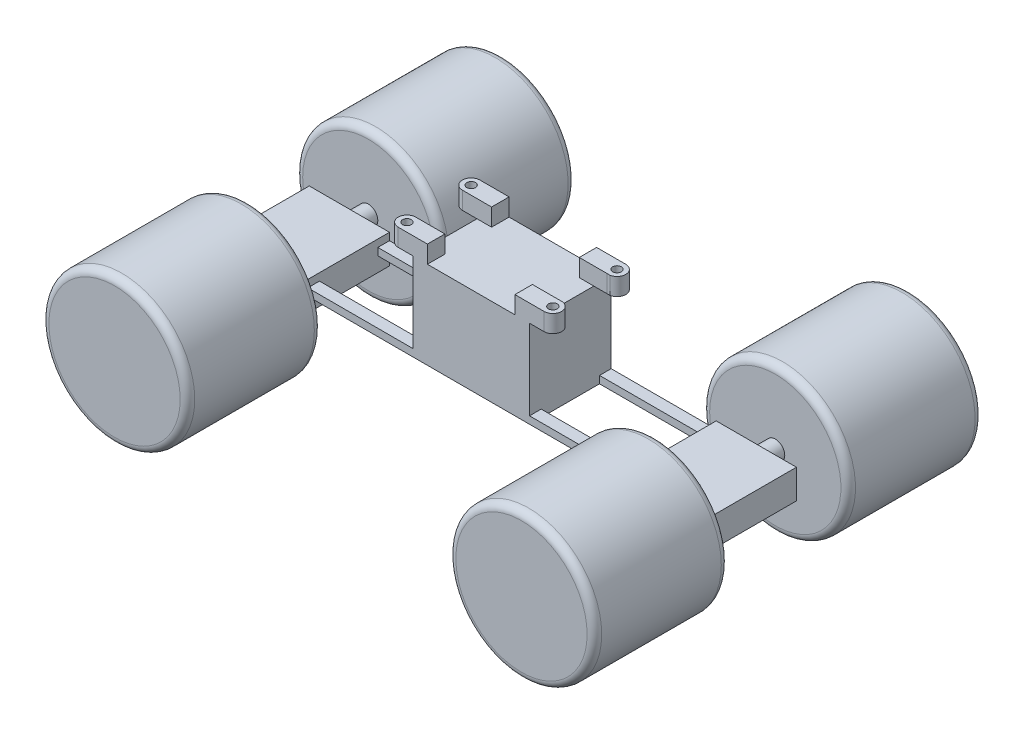
SolidWorks part; units mm, degrees
ref_plane "Front Plane" through (0, 0, 0) normal (0, 0, 1) x (1, 0, 0)
ref_plane "Top Plane" through (0, 0, 0) normal (0, 1, 0) x (1, 0, 0)
ref_plane "Right Plane" through (0, 0, 0) normal (1, 0, 0) x (0, 0, -1)
sketch "Sketch1" plane through (0, 0, 0) normal (0, 1, 0) x (1, 0, 0)
  line L0 (0, 50) -> (20, 50)
  line L1 (0, 38) -> (20, 38)
  line L2 (0, 6) -> (20, 6)
  line L3 (20, 6) -> (20, -6)
  line L4 (20, -6) -> (0, -6)
  line L5 (20, 50) -> (20, 38)
  line L6 (100, 50) -> (80, 50)
  line L7 (80, 50) -> (80, 38.1072)
  line L8 (101.0693, 38.0961) -> (98.8708, 38.1072)
  line L9 (80, 38.1072) -> (101.0693, 38.0961)
  line L10 (100, 6) -> (80, 6)
  line L11 (80, 6) -> (80, -6)
  line L12 (80, -6) -> (100, -6)
  circle A0 centre (0, 0) radius 3
  circle A1 centre (0, 44) radius 3
  circle A2 centre (100, 44) radius 3
  circle A3 centre (100, 0) radius 3
  arc A4 (0, 50) -> (0, 38) centre (0, 44) ccw
  arc A5 (0, 6) -> (0, -6) centre (0, 0) ccw
  arc A6 (100, -6) -> (100, 6) centre (100, 0) ccw
  arc A7 (98.8708, 38.1072) -> (100, 50) centre (100, 44) ccw
extrude "Boss-Extrude1" add sketch "Sketch1" against normal blind 12 contours L0 A4 L1 L5 A1 | L2 A5 L4 L3 A0 | L12 A6 L10 L11 A3 | L8 A7 L6 L7 L9 A2
sketch "Sketch2" plane through (0, -12, 0) normal (0, -1, 0) x (1, 0, 0)
  line L0 (20, 6) -> (10, 6)
  line L1 (20, 6) -> (0, 6) construction
  line L2 (10, 6) -> (10, -50)
  line L3 (0, -50) -> (20, -50) construction
  line L4 (80, 6) -> (90, 6)
  line L5 (80, 6) -> (100, 6) construction
  line L6 (90, 6) -> (90, -50)
  line L7 (100, -50) -> (80, -50) construction
  line L8 (90, -50) -> (10, -50)
  line L9 (20, 6) -> (80, 6)
extrude "Boss-Extrude2" add sketch "Sketch2" along normal blind 60
sketch "Sketch3" plane through (0, 0, 6) normal (0, 0, 1) x (1, 0, 0)
  line L0 (10, -72) -> (-62, -72)
  line L1 (90, -72) -> (10, -72) construction
  line L2 (50, -72) -> (50, -12) construction
  line L3 (80, -12) -> (20, -12) construction
  line L4 (-62, -67) -> (-62, -62)
  line L5 (-62, -72) -> (-62, -82)
  line L6 (-62, -82) -> (-117, -82)
  line L7 (-117, -82) -> (-117, -62)
  line L8 (-117, -62) -> (-62, -62)
  line L9 (-62, -67) -> (10, -67)
  line L10 (10, -72) -> (10, -12) construction
  line L11 (10, -67) -> (10, -72)
  line L12 (90, -67) -> (90, -72)
  line L13 (162, -67) -> (90, -67)
  line L14 (217, -62) -> (162, -62)
  line L15 (217, -82) -> (217, -62)
  line L16 (162, -82) -> (217, -82)
  line L17 (162, -72) -> (162, -82)
  line L18 (162, -67) -> (162, -62)
  line L19 (90, -72) -> (162, -72)
  dimension "D1" = 0
extrude "Boss-Extrude3" add sketch "Sketch3" against normal blind 8
ref_plane "Plane1" through (0, 0, -22) normal (0, 0, 1) x (1, 0, 0)
mirror "Mirror1" about plane through (0, 0, -22) normal (0, 0, 1) of "Boss-Extrude3"
sketch "Sketch4" plane through (0, 0, -42) normal (0, 0, 1) x (1, 0, 0)
  line L1 (-117, -62) -> (-62, -62)
  line L2 (-117, -62) -> (-117, -82)
  line L3 (-117, -82) -> (-62, -82)
  line L4 (-62, -62) -> (-62, -82)
  line L5 (162, -62) -> (217, -62)
  line L6 (162, -62) -> (162, -82)
  line L7 (162, -82) -> (217, -82)
  line L8 (217, -62) -> (217, -82)
extrude "Boss-Extrude4" add sketch "Sketch4" along normal blind 48
sketch "Sketch5" plane through (0, 0, 6) normal (0, 0, 1) x (1, 0, 0)
  line L0 (-117, -72) -> (-62, -72) construction
  line L1 (-117, -62) -> (-117, -82) construction
  line L2 (-89.5, -62) -> (-89.5, -82) construction
  line L3 (-62, -62) -> (-117, -62) construction
  line L4 (-117, -82) -> (-62, -82) construction
  line L5 (217, -72) -> (162, -72) construction
  line L6 (217, -82) -> (217, -62) construction
  circle A0 centre (-89.5, -72) radius 6.5
  circle A1 centre (189.5, -72) radius 6.5
extrude "Boss-Extrude5" add sketch "Sketch5" along normal blind 13
sketch "Sketch6" plane through (0, 0, 19) normal (0, 0, 1) x (1, 0, 0)
  circle A0 centre (-89.5, -72) radius 50
  circle A1 centre (189.5, -72) radius 50
extrude "Boss-Extrude6" add sketch "Sketch6" along normal blind 92
fillet "Fillet2" radius 5 4 edges at (239.5, -72, 111) (239.5, -72, 19) (-39.5, -72, 19) (-39.5, -72, 111)
mirror "Mirror2" about plane through (0, 0, -22) normal (0, 0, 1) of "Boss-Extrude5", "Boss-Extrude6", "Fillet2"
